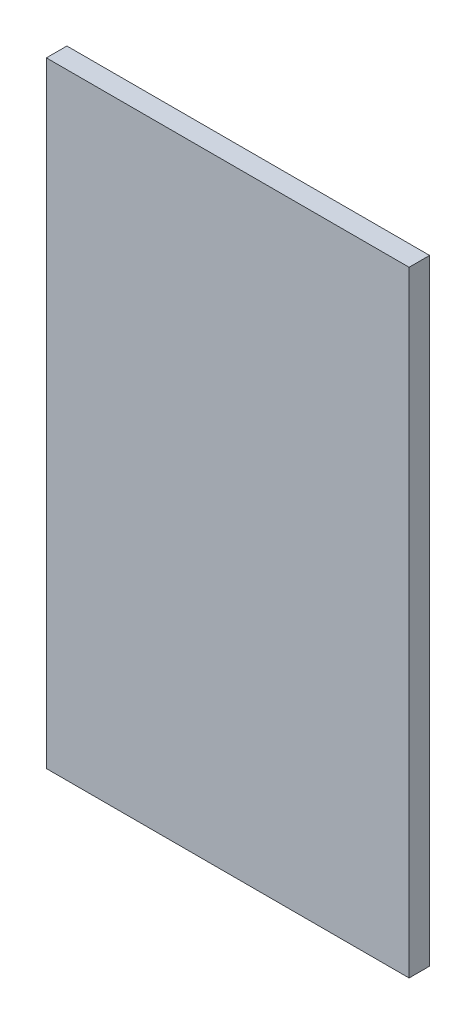
SolidWorks part; units mm, degrees
ref_plane "정면" through (0, 0, 0) normal (0, 0, 1) x (1, 0, 0)
ref_plane "윗면" through (0, 0, 0) normal (0, 1, 0) x (1, 0, 0)
ref_plane "우측면" through (0, 0, 0) normal (1, 0, 0) x (0, 0, -1)
sketch "스케치1" plane through (0, 0, 0) normal (0, 0, 1) x (1, 0, 0)
  line L1 (-44.195, -75) -> (44.195, -75)
  line L2 (-44.195, -75) -> (-44.195, 75)
  line L3 (-44.195, 75) -> (44.195, 75)
  line L4 (44.195, -75) -> (44.195, 75)
  line L5 (-44.195, -75) -> (44.195, 75) construction
  line L6 (-44.195, 75) -> (44.195, -75) construction
  point P0 (0, 0)
  dimension "D1" = 88.39
  dimension "D2" = 150
extrude "보스-돌출1" add sketch "스케치1" along normal blind 5
